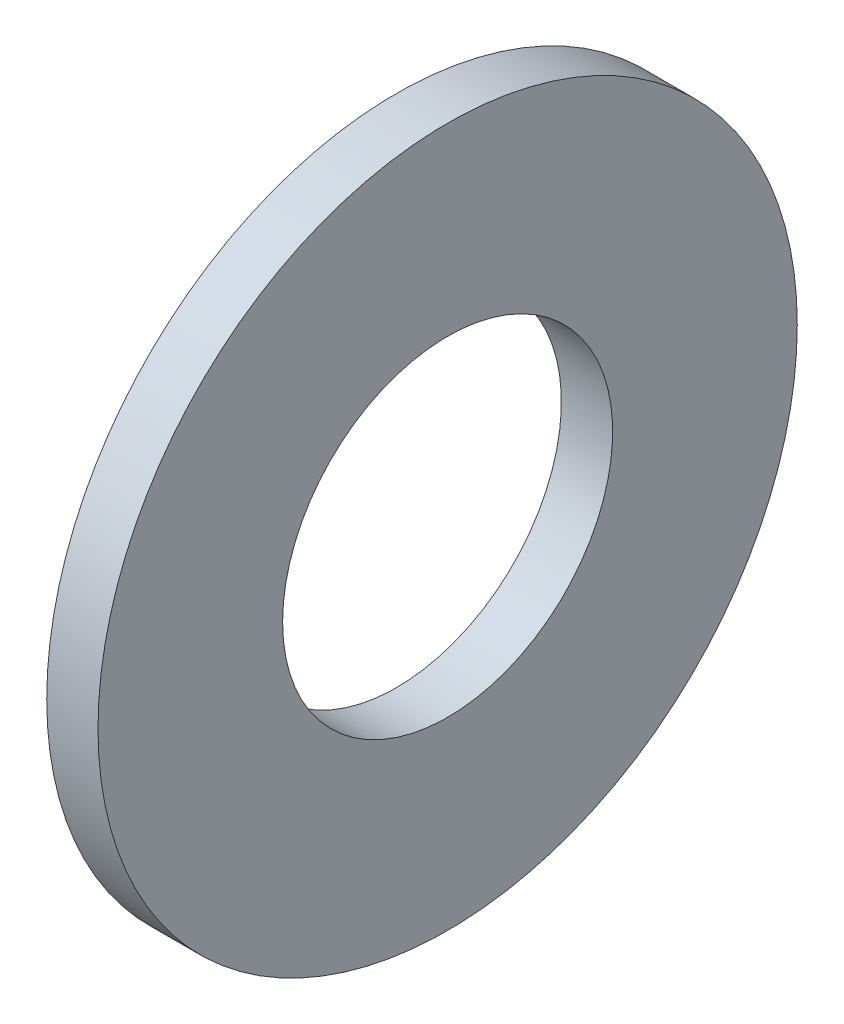
SolidWorks part; units mm, degrees
ref_plane "Plane1" through (0, 0, 0) normal (0, 0, 1) x (1, 0, 0)
ref_plane "Plane2" through (0, 0, 0) normal (0, 1, 0) x (1, 0, 0)
ref_plane "Plane3" through (0, 0, 0) normal (1, 0, 0) x (0, 0, -1)
sketch "Sketch1" plane through (0, 0, 0) normal (0, 0, 1) x (1, 0, 0)
  line L0 (-34.925, 0) -> (9.525, 0) construction
  line L1 (0, 13.4874) -> (0, 28.575)
  line L2 (0, 28.575) -> (-4.191, 28.575)
  line L3 (-4.191, 28.575) -> (-4.191, 13.4874)
  line L4 (-4.191, 13.4874) -> (0, 13.4874)
  dimension "Thickness" = 4.191
  dimension "Inside_dia" = 26.9748
  dimension "Outside_dia" = 57.15
revolve "Base-Revolve" add sketch "Sketch1" angle 360 about L0
